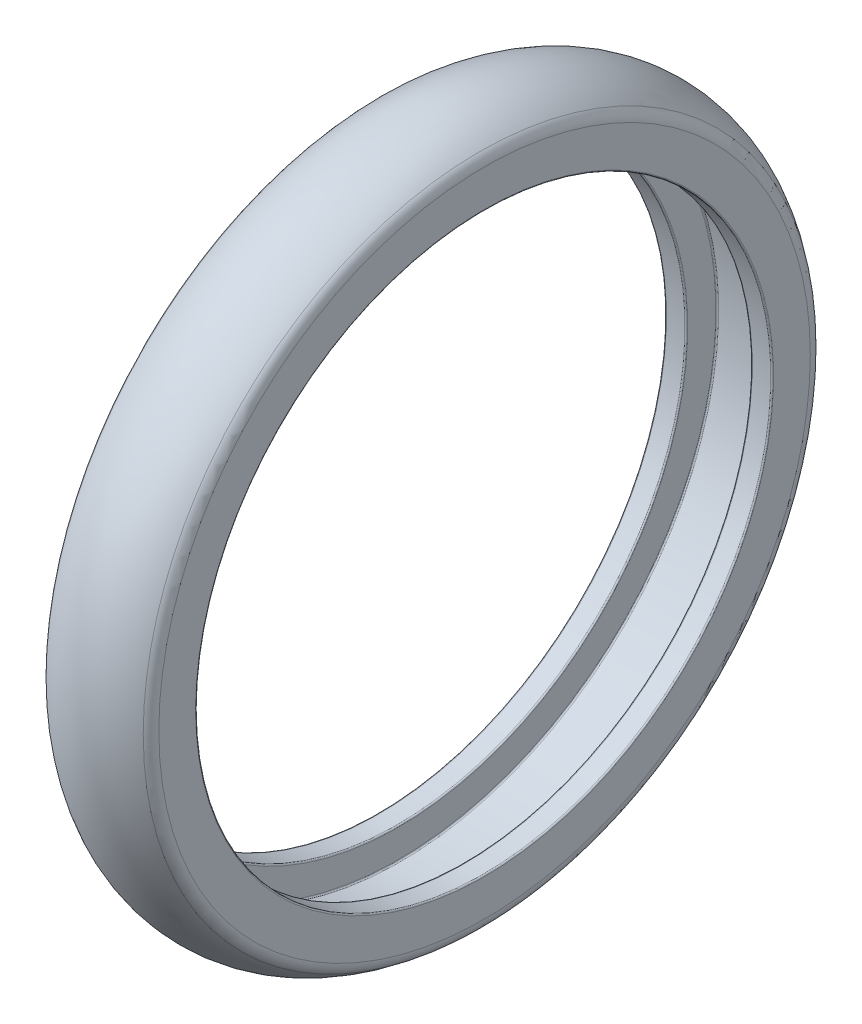
SolidWorks part; units mm, degrees
ref_plane "Front Plane" through (0, 0, 0) normal (0, 0, 1) x (1, 0, 0)
ref_plane "Top Plane" through (0, 0, 0) normal (0, 1, 0) x (1, 0, 0)
ref_plane "Right Plane" through (0, 0, 0) normal (1, 0, 0) x (0, 0, -1)
sketch "Sketch1" plane through (0, 0, 0) normal (0, 0, 1) x (1, 0, 0)
  line L0 (0, 18.288) -> (0, -18.288) construction
  line L1 (-1.7748, 18.288) -> (1.7748, 18.288)
  line L2 (-3.0734, 16.51) -> (3.0734, 16.51) construction
  line L3 (0, 0) -> (3.0734, 0) construction
  line L4 (3.0734, -16.51) -> (3.0734, 16.51) construction
  line L5 (1.8542, 18.2086) -> (1.8542, 16.5894)
  line L6 (1.9336, 16.51) -> (2.994, 16.51)
  line L7 (-1.8542, 18.2086) -> (-1.8542, 16.5894)
  line L8 (-1.9336, 16.51) -> (-2.994, 16.51)
  line L9 (-3.0734, 16.5894) -> (-3.0734, 18.7006)
  line L10 (3.0734, 16.5894) -> (3.0734, 18.7006)
  arc A0 (-2.7879, 19.3103) -> (2.7879, 19.3103) centre (0, 15.9662) cw
  arc A1 (3.0734, 18.7006) -> (2.7879, 19.3103) centre (2.2797, 18.7006) ccw
  arc A2 (-2.7879, 19.3103) -> (-3.0734, 18.7006) centre (-2.2797, 18.7006) ccw
  arc A3 (3.0734, 16.5894) -> (2.994, 16.51) centre (2.994, 16.5894) cw
  arc A4 (1.9336, 16.51) -> (1.8542, 16.5894) centre (1.9336, 16.5894) cw
  arc A5 (1.8542, 18.2086) -> (1.7748, 18.288) centre (1.7748, 18.2086) ccw
  arc A6 (-1.7748, 18.288) -> (-1.8542, 18.2086) centre (-1.7748, 18.2086) ccw
  arc A7 (-1.8542, 16.5894) -> (-1.9336, 16.51) centre (-1.9336, 16.5894) cw
  arc A8 (-2.994, 16.51) -> (-3.0734, 16.5894) centre (-2.994, 16.5894) cw
  point P4 (0, 0)
  point P8 (0, 18.288)
  point P11 (0, 16.51)
  point P16 (3.0734, 0)
  point P20 (0, 20.32)
  point P22 (3.0734, 19.05)
  point P30 (1.8542, 16.51)
  point P33 (1.8542, 18.288)
  point P36 (-1.8542, 18.288)
  point P39 (-1.8542, 16.51)
  dimension "D7" = 0.7937
  dimension "D8" = 0.0794
  dimension "D1" = 36.576
  dimension "D2" = 3.7084
  dimension "D3" = 33.02
  dimension "D4" = 6.1468
  dimension "D5" = 20.32
  dimension "D6" = 19.05
revolve "Revolve1" add sketch "Sketch1" angle 360 about L3
